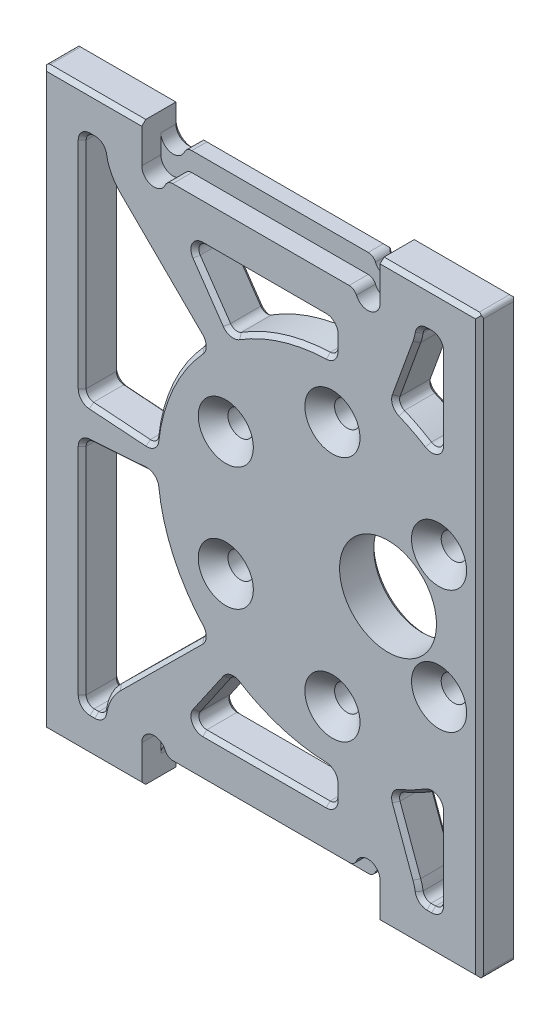
SolidWorks part; units mm, degrees
ref_plane "Front Plane" through (0, 0, 0) normal (0, 0, 1) x (1, 0, 0)
ref_plane "Top Plane" through (0, 0, 0) normal (0, 1, 0) x (1, 0, 0)
ref_plane "Right Plane" through (0, 0, 0) normal (1, 0, 0) x (0, 0, -1)
sketch "Sketch1" plane through (0, 0, 0) normal (0, 0, 1) x (1, 0, 0)
  line L24 (23.8172, 72.7248) -> (0.0172, 72.7248)
  line L25 (26.9172, 75.1248) -> (26.9172, 72.7248)
  line L26 (39.4172, 75.1248) -> (26.9172, 75.1248)
  line L27 (39.4172, 2.6248) -> (39.4172, 75.1248)
  line L28 (26.9172, 2.6248) -> (39.4172, 2.6248)
  line L29 (26.9172, 5.0248) -> (26.9172, 2.6248)
  line L30 (0.0172, 5.0248) -> (23.8172, 5.0248)
  line L31 (-3.0828, 2.6248) -> (-3.0828, 5.0248)
  line L32 (-15.5828, 2.6248) -> (-3.0828, 2.6248)
  line L33 (-15.5828, 75.1248) -> (-15.5828, 2.6248)
  line L34 (-3.0828, 75.1248) -> (-15.5828, 75.1248)
  line L35 (-3.0828, 72.7248) -> (-3.0828, 75.1248)
  line L36 (23.8172, 72.7248) -> (0.0172, 72.7248)
  line L37 (26.9172, 75.1248) -> (26.9172, 72.7248)
  line L38 (39.4172, 75.1248) -> (26.9172, 75.1248)
  line L39 (39.4172, 2.6248) -> (39.4172, 75.1248)
  line L40 (26.9172, 2.6248) -> (39.4172, 2.6248)
  line L41 (26.9172, 5.0248) -> (26.9172, 2.6248)
  line L42 (0.0172, 5.0248) -> (23.8172, 5.0248)
  line L43 (-3.0828, 2.6248) -> (-3.0828, 5.0248)
  line L44 (-15.5828, 2.6248) -> (-3.0828, 2.6248)
  line L45 (-15.5828, 75.1248) -> (-15.5828, 2.6248)
  line L46 (-3.0828, 75.1248) -> (-15.5828, 75.1248)
  line L47 (-3.0828, 72.7248) -> (-3.0828, 75.1248)
  circle A1 centre (20.9172, 38.8748) radius 15.5 construction
  circle A2 centre (20.9172, 54.3748) radius 1.6
  circle A18 centre (34.3406, 46.6248) radius 1.6
  arc A20 (23.8172, 72.7248) -> (26.9172, 72.7248) centre (25.3672, 72.7248) ccw
  arc A21 (26.9172, 5.0248) -> (23.8172, 5.0248) centre (25.3672, 5.0248) ccw
  arc A22 (0.0172, 5.0248) -> (-3.0828, 5.0248) centre (-1.5328, 5.0248) ccw
  arc A23 (-3.0828, 72.7248) -> (0.0172, 72.7248) centre (-1.5328, 72.7248) ccw
  arc A24 (23.8172, 72.7248) -> (26.9172, 72.7248) centre (25.3672, 72.7248) ccw
  arc A25 (26.9172, 5.0248) -> (23.8172, 5.0248) centre (25.3672, 5.0248) ccw
  arc A26 (0.0172, 5.0248) -> (-3.0828, 5.0248) centre (-1.5328, 5.0248) ccw
  arc A27 (-3.0828, 72.7248) -> (0.0172, 72.7248) centre (-1.5328, 72.7248) ccw
  circle A38 centre (34.3406, 31.1248) radius 1.6
  circle A39 centre (20.9172, 23.3748) radius 1.6
  circle A40 centre (7.4939, 31.1248) radius 1.6
  circle A41 centre (7.4939, 46.6248) radius 1.6
  circle A62 centre (27.9172, 38.8748) radius 6.1
  point P62 (20.9172, 38.8748)
  dimension "D4" = 31
  dimension "D5" = 3.2
  dimension "D7" = 7.75
  dimension "D9" = 12.2
  dimension "D2" = 36.5
  dimension "D3" = 33.85
  dimension "D8" = 13.4234
  dimension "D10" = 7
  dimension "D1" = 0
  dimension "D6" = 6
extrude "Boss-Extrude1" add sketch "Sketch1" along normal blind 4.8
chamfer "Chamfer1" distance 1.87 angle 45 6 edges at (9.0939, 31.1248, 4.8) (22.5172, 54.3748, 4.8) (35.9406, 46.6248, 4.8) (35.9406, 31.1248, 4.8) (22.5172, 23.3748, 4.8) (9.0939, 46.6248, 4.8)
sketch "Sketch2" plane through (0, 0, 4.8) normal (0, 0, 1) x (1, 0, 0)
  line L0 (23.8172, 72.7248) -> (0.0172, 72.7248) construction
  line L1 (26.9172, 72.7248) -> (26.9172, 70.3248) construction
  line L2 (23.8172, 70.3248) -> (0.0172, 70.3248) construction
  line L3 (-3.0828, 70.3248) -> (-3.0828, 72.7248) construction
  line L4 (23.8172, 72.7248) -> (0.0172, 72.7248)
  line L5 (26.9172, 72.7248) -> (26.9172, 70.3248)
  line L6 (23.8172, 70.3248) -> (0.0172, 70.3248)
  line L7 (-3.0828, 70.3248) -> (-3.0828, 72.7248)
  line L8 (26.9172, 5.0248) -> (26.9172, 7.4248) construction
  line L9 (-3.0828, 7.4248) -> (-3.0828, 5.0248) construction
  line L10 (23.8172, 7.4248) -> (0.0172, 7.4248) construction
  line L11 (0.0172, 5.0248) -> (23.8172, 5.0248) construction
  line L12 (26.9172, 5.0248) -> (26.9172, 7.4248)
  line L13 (-3.0828, 7.4248) -> (-3.0828, 5.0248)
  line L14 (23.8172, 7.4248) -> (0.0172, 7.4248)
  line L15 (0.0172, 5.0248) -> (23.8172, 5.0248)
  arc A0 (-3.0828, 72.7248) -> (0.0172, 72.7248) centre (-1.5328, 72.7248) ccw construction
  arc A1 (23.8172, 72.7248) -> (26.9172, 72.7248) centre (25.3672, 72.7248) ccw construction
  arc A2 (23.8172, 70.3248) -> (26.9172, 70.3248) centre (25.3672, 70.3248) ccw construction
  arc A3 (-3.0828, 70.3248) -> (0.0172, 70.3248) centre (-1.5328, 70.3248) ccw construction
  arc A4 (-3.0828, 72.7248) -> (0.0172, 72.7248) centre (-1.5328, 72.7248) ccw
  arc A5 (23.8172, 72.7248) -> (26.9172, 72.7248) centre (25.3672, 72.7248) ccw
  arc A6 (23.8172, 70.3248) -> (26.9172, 70.3248) centre (25.3672, 70.3248) ccw
  arc A7 (-3.0828, 70.3248) -> (0.0172, 70.3248) centre (-1.5328, 70.3248) ccw
  arc A8 (26.9172, 7.4248) -> (23.8172, 7.4248) centre (25.3672, 7.4248) ccw construction
  arc A9 (26.9172, 5.0248) -> (23.8172, 5.0248) centre (25.3672, 5.0248) ccw construction
  arc A10 (0.0172, 7.4248) -> (-3.0828, 7.4248) centre (-1.5328, 7.4248) ccw construction
  arc A11 (0.0172, 5.0248) -> (-3.0828, 5.0248) centre (-1.5328, 5.0248) ccw construction
  arc A12 (26.9172, 7.4248) -> (23.8172, 7.4248) centre (25.3672, 7.4248) ccw
  arc A13 (26.9172, 5.0248) -> (23.8172, 5.0248) centre (25.3672, 5.0248) ccw
  arc A14 (0.0172, 7.4248) -> (-3.0828, 7.4248) centre (-1.5328, 7.4248) ccw
  arc A15 (0.0172, 5.0248) -> (-3.0828, 5.0248) centre (-1.5328, 5.0248) ccw
extrude "Cut-Extrude1" cut sketch "Sketch2" against normal blind 2.4
sketch "Sketch5" plane through (0, 0, 4.8) normal (0, 0, 1) x (1, 0, 0)
  line L12 (20.9172, 38.8748) -> (31.524, 68.0895) construction
  line L13 (20.9172, 38.8748) -> (21.1361, 65.3248) construction
  line L14 (20.9172, 38.8748) -> (2.6984, 65.3248) construction
  line L15 (20.9172, 38.8748) -> (-6.1416, 65.6707) construction
  line L16 (20.9172, 38.8748) -> (-6.1416, 12.0789) construction
  line L17 (20.9172, 38.8748) -> (2.6984, 12.4248) construction
  line L18 (20.9172, 38.8748) -> (21.1361, 12.4248) construction
  line L19 (20.9172, 38.8748) -> (31.524, 9.6601) construction
  line L20 (-15.5828, 38.8748) -> (39.4172, 38.8748) construction
  line L21 (-15.5828, 75.1248) -> (-15.5828, 2.6248) construction
  line L22 (39.4172, 2.6248) -> (39.4172, 75.1248) construction
  line L23 (20.9172, 38.8748) -> (-10.5828, 41.0775) construction
  line L24 (21.1361, 65.3248) -> (2.6984, 65.3248)
  line L25 (-8.0797, 70.1248) -> (-10.5828, 70.1248)
  line L26 (-10.5828, 70.1248) -> (-10.5828, 7.6248)
  line L27 (-10.5828, 7.6248) -> (-8.0797, 7.6248)
  line L28 (2.6984, 12.4248) -> (21.1361, 12.4248)
  line L29 (31.9142, 7.6248) -> (34.4172, 7.6248)
  line L30 (34.4172, 7.6248) -> (34.4172, 70.1248)
  line L31 (34.4172, 70.1248) -> (31.9142, 70.1248)
  line L32 (21.1361, 65.3248) -> (2.6984, 65.3248)
  line L33 (-8.0797, 70.1248) -> (-10.5828, 70.1248)
  line L34 (-10.5828, 70.1248) -> (-10.5828, 41.0775)
  line L35 (-10.5828, 7.6248) -> (-8.0797, 7.6248)
  line L36 (2.6984, 12.4248) -> (21.1361, 12.4248)
  line L37 (31.9142, 7.6248) -> (34.4172, 7.6248)
  line L38 (34.4172, 7.6248) -> (34.4172, 20.8748)
  line L39 (34.4172, 70.1248) -> (31.9142, 70.1248)
  line L40 (20.9172, 38.8748) -> (-10.5828, 36.6721) construction
  line L41 (31.524, 68.0895) -> (28.5958, 60.024)
  line L42 (21.1361, 65.3248) -> (21.1034, 61.374)
  line L43 (2.6984, 65.3248) -> (8.1539, 57.4044)
  line L44 (-6.1416, 65.6707) -> (4.9298, 54.7068)
  line L45 (-10.5828, 41.0775) -> (-1.5279, 40.4443)
  line L46 (-10.5828, 36.6721) -> (-1.5279, 37.3052)
  line L47 (-6.1416, 12.0789) -> (4.9298, 23.0427)
  line L48 (2.6984, 12.4248) -> (8.1539, 20.3451)
  line L49 (21.1361, 12.4248) -> (21.1034, 16.3755)
  line L50 (31.524, 9.6601) -> (28.5958, 17.7255)
  line L51 (-10.5828, 36.6721) -> (-10.5828, 7.6248)
  line L52 (34.4172, 56.8748) -> (34.4172, 70.1248)
  circle A0 centre (20.9172, 38.8748) radius 22.5 construction
  arc A5 (8.1539, 20.3451) -> (21.1034, 16.3755) centre (20.9172, 38.8748) ccw
  arc A6 (-8.0797, 70.1248) -> (-6.1416, 65.6707) centre (-1.5328, 70.3248) ccw
  arc A7 (31.524, 68.0895) -> (31.9142, 70.1248) centre (25.3672, 70.3248) ccw
  arc A8 (31.9142, 7.6248) -> (31.524, 9.6601) centre (25.3672, 7.4248) ccw
  arc A9 (21.1361, 65.3248) -> (31.9142, 70.1248) centre (25.3672, 70.3248) ccw
  arc A10 (-8.0797, 70.1248) -> (2.6984, 65.3248) centre (-1.5328, 70.3248) ccw
  arc A11 (2.6984, 12.4248) -> (-8.0797, 7.6248) centre (-1.5328, 7.4248) ccw
  arc A12 (31.9142, 7.6248) -> (21.1361, 12.4248) centre (25.3672, 7.4248) ccw
  arc A13 (21.1361, 65.3248) -> (31.9142, 70.1248) centre (25.3672, 70.3248) ccw construction
  arc A14 (-8.0797, 70.1248) -> (2.6984, 65.3248) centre (-1.5328, 70.3248) ccw construction
  arc A15 (2.6984, 12.4248) -> (-8.0797, 7.6248) centre (-1.5328, 7.4248) ccw construction
  arc A16 (31.9142, 7.6248) -> (21.1361, 12.4248) centre (25.3672, 7.4248) ccw construction
  arc A17 (-6.1416, 12.0789) -> (-8.0797, 7.6248) centre (-1.5328, 7.4248) ccw
  arc A18 (-1.5279, 37.3052) -> (4.9298, 23.0427) centre (20.9172, 38.8748) ccw
  arc A19 (4.9298, 54.7068) -> (-1.5279, 40.4443) centre (20.9172, 38.8748) ccw
  arc A20 (21.1034, 61.374) -> (8.1539, 57.4044) centre (20.9172, 38.8748) ccw
  arc A21 (34.4172, 56.8748) -> (28.5958, 60.024) centre (20.9172, 38.8748) ccw
  arc A22 (28.5958, 17.7255) -> (34.4172, 20.8748) centre (20.9172, 38.8748) ccw
  dimension "D1" = 45
  dimension "D3" = 8
  dimension "D4" = 4
  dimension "D2" = 5
extrude "Cut-Extrude3" cut sketch "Sketch5" against normal up to next
fillet "Fillet1" radius 1 26 edges at (31.9142, 7.6248, 2.4) (28.5958, 17.7255, 2.4) (34.4172, 20.8748, 2.4) (21.1034, 16.3755, 2.4) (8.1539, 20.3451, 2.4) (2.6984, 12.4248, 2.4) (34.4172, 7.6248, 2.4) (21.1361, 12.4248, 2.4) (-8.0797, 7.6248, 2.4) (4.9298, 23.0427, 2.4) (-1.5279, 37.3052, 2.4) (-10.5828, 36.6721, 2.4) (-10.5828, 7.6248, 2.4) (-10.5828, 41.0775, 2.4) (-8.0797, 70.1248, 2.4) (-10.5828, 70.1248, 2.4) (-1.5279, 40.4443, 2.4) (4.9298, 54.7068, 2.4) (21.1034, 61.374, 2.4) (8.1539, 57.4044, 2.4) (2.6984, 65.3248, 2.4) (21.1361, 65.3248, 2.4) (28.5958, 60.024, 2.4) (34.4172, 56.8748, 2.4) (34.4172, 70.1248, 2.4) (31.9142, 70.1248, 2.4)
sketch "Sketch3" plane through (0, 0, 0) normal (0, 0, -1) x (-1, 0, 0)
  text T0 "<b>gen3.0.0</b>"
extrude "Cut-Extrude2" cut sketch "Sketch3" against normal blind 0.5
chamfer "Chamfer2" distance 0.5 angle 45 141 edges at (34.0172, 38.8748, 0) (34.4172, 63.9496, 0) (34.1244, 69.8319, 0) (33.901, 57.8993, 0) (33.1193, 70.1248, 0) (31.2243, 58.8751, 0) (32.1728, 69.886, 0) (28.955, 60.1987, 0) (31.7072, 68.6793, 0) (30.2269, 64.5167, 0) (21.1196, 63.3346, 0) (20.8278, 61.6631, 0) (20.8378, 65.0289, 0) (14.3229, 60.3867, 0) (12.3646, 65.3248, 0) (8.2202, 57.7983, 0) (3.7162, 64.7899, 0) (5.6883, 60.984, 0) (-7.3578, 67.3295, 0) (-8.3383, 69.886, 0) (-0.9536, 60.5331, 0) (-9.2848, 70.1248, 0) (4.5304, 54.7111, 0) (-10.2899, 69.8319, 0) (0.4204, 48.1553, 0) (-10.5828, 55.5674, 0) (-1.7947, 40.7416, 0) (-10.3141, 41.328, 0) (-6.0784, 40.7625, 0) (-10.3141, 36.4216, 0) (-10.5828, 22.1822, 0) (-6.0784, 36.987, 0) (-10.2899, 7.9177, 0) (-1.7947, 37.0079, 0) (-9.2848, 7.6248, 0) (0.4204, 29.5942, 0) (-8.3383, 7.8635, 0) (4.5304, 23.0385, 0) (-7.3578, 10.42, 0) (-0.9536, 17.2165, 0) (14.3229, 17.3628, 0) (20.8278, 16.0864, 0) (8.2202, 19.9512, 0) (21.1196, 14.4149, 0) (5.6883, 16.7656, 0) (20.8378, 12.7206, 0) (3.7162, 12.9596, 0) (12.3646, 12.4248, 0) (30.2269, 13.2328, 0) (31.7072, 9.0703, 0) (28.955, 17.5508, 0) (32.1728, 7.8635, 0) (31.2243, 18.8744, 0) (33.1193, 7.6248, 0) (33.901, 19.8502, 0) (34.1244, 7.9177, 0) (34.4172, 13.7999, 0) (11.9172, 5.0248, 0) (-1.5328, 6.5748, 0) (-3.0828, 3.8248, 0) (-9.3328, 2.6248, 4.8) (-1.5328, 71.1748, 0) (-15.5828, 38.8748, 0) (-9.3328, 75.1248, 0) (-3.0828, 73.9248, 0) (11.9172, 72.7248, 0) (25.3672, 6.5748, 0) (25.3672, 71.1748, 0) (26.9172, 3.8248, 0) (33.1672, 2.6248, 0) (39.4172, 38.8748, 0) (26.9172, 73.9248, 0) (33.1672, 75.1248, 0) (35.9406, 46.6248, 0) (22.5172, 54.3748, 0) (9.0939, 46.6248, 0) (9.0939, 31.1248, 0) (22.5172, 23.3748, 0) (35.9406, 31.1248, 0) (-9.3328, 2.6248, 0) (-10.5828, 22.1822, 4.8) (-10.3141, 36.4216, 4.8) (-10.2899, 7.9177, 4.8) (-6.0784, 36.987, 4.8) (-9.2848, 7.6248, 4.8) (-1.7947, 37.0079, 4.8) (-8.3383, 7.8635, 4.8) (0.4204, 29.5942, 4.8) (-7.3578, 10.42, 4.8) (4.5304, 23.0385, 4.8) (-0.9536, 17.2165, 4.8) (14.3229, 17.3628, 4.8) (8.2202, 19.9512, 4.8) (20.8278, 16.0864, 4.8) (5.6883, 16.7656, 4.8) (21.1196, 14.4149, 4.8) (3.7162, 12.9596, 4.8) (20.8378, 12.7206, 4.8) (12.3646, 12.4248, 4.8) (31.7072, 9.0703, 4.8) (30.2269, 13.2328, 4.8) (32.1728, 7.8635, 4.8) (28.955, 17.5508, 4.8) (33.1193, 7.6248, 4.8) (31.2243, 18.8744, 4.8) (34.1244, 7.9177, 4.8) (33.901, 19.8502, 4.8) (34.4172, 13.7999, 4.8) (30.2269, 64.5167, 4.8) (31.7072, 68.6793, 4.8) (28.955, 60.1987, 4.8) (32.1728, 69.886, 4.8) (31.2243, 58.8751, 4.8) (33.1193, 70.1248, 4.8) (33.901, 57.8993, 4.8) (34.1244, 69.8319, 4.8) (34.4172, 63.9496, 4.8) (14.3229, 60.3867, 4.8) (20.8278, 61.6631, 4.8) (8.2202, 57.7983, 4.8) (21.1196, 63.3346, 4.8) (5.6883, 60.984, 4.8) (20.8378, 65.0289, 4.8) (3.7162, 64.7899, 4.8) (12.3646, 65.3248, 4.8) (-0.9536, 60.5331, 4.8) (4.5304, 54.7111, 4.8) (-7.3578, 67.3295, 4.8) (0.4204, 48.1553, 4.8) (-8.3383, 69.886, 4.8) (-1.7947, 40.7416, 4.8) (-9.2848, 70.1248, 4.8) (-6.0784, 40.7625, 4.8) (-10.2899, 69.8319, 4.8) (-10.3141, 41.328, 4.8) (-10.5828, 55.5674, 4.8) (33.1672, 2.6248, 4.8) (39.4172, 38.8748, 4.8) (33.1672, 75.1248, 4.8) (-9.3328, 75.1248, 4.8) (-15.5828, 38.8748, 4.8)
fillet "Fillet2" radius 1 8 edges at (0.0172, 7.4248, 3.6) (0.0172, 5.0248, 1.45) (23.8172, 5.0248, 1.45) (23.8172, 7.4248, 3.6) (23.8172, 70.3248, 3.6) (23.8172, 72.7248, 1.45) (0.0172, 70.3248, 3.6) (0.0172, 72.7248, 1.45)
fillet "Fillet3" radius 0.5 4 edges at (-15.5828, 75.1248, 2.4) (39.4172, 75.1248, 2.4) (-15.5828, 2.6248, 2.4) (39.4172, 2.6248, 2.4)
equation "\"´0.50mm\"=1"
